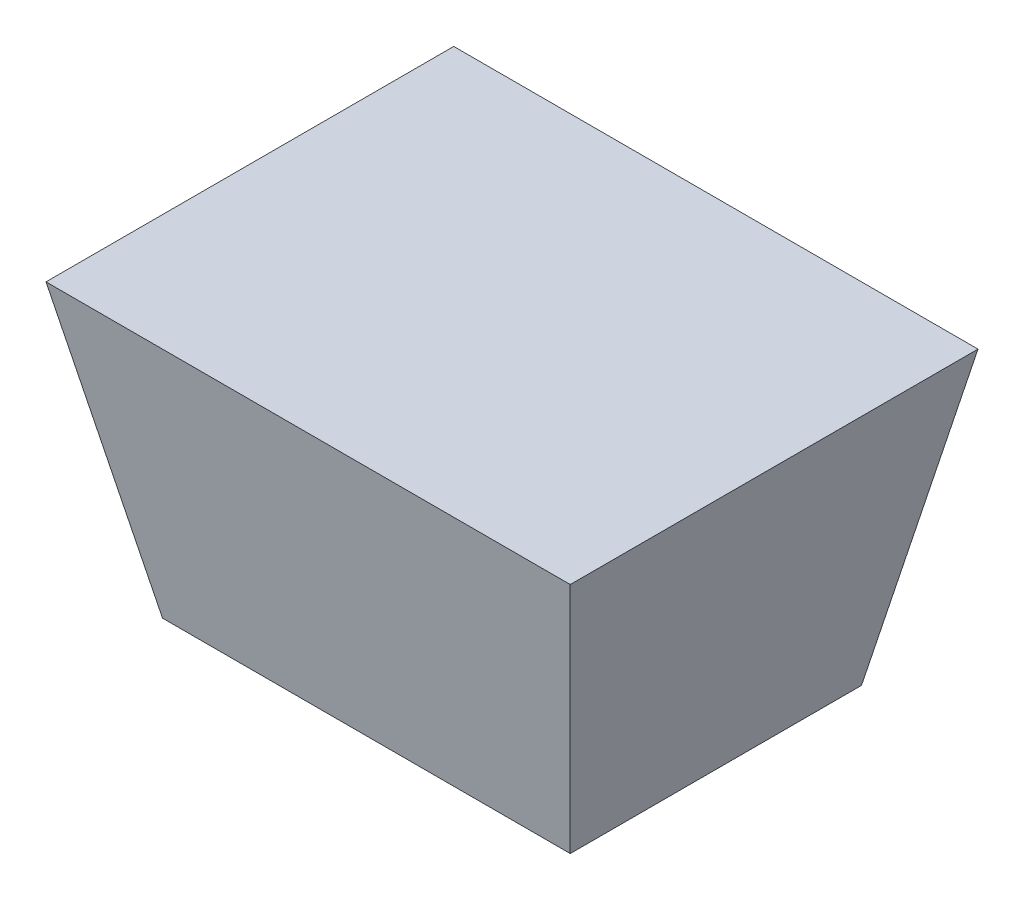
SolidWorks part; units mm, degrees
ref_plane "Front Plane" through (0, 0, 0) normal (0, 0, 1) x (1, 0, 0)
ref_plane "Top Plane" through (0, 0, 0) normal (0, 1, 0) x (1, 0, 0)
ref_plane "Right Plane" through (0, 0, 0) normal (1, 0, 0) x (0, 0, -1)
sketch "Sketch1" plane through (0, 0, 0) normal (0, 1, 0) x (1, 0, 0)
  line L1 (-35, 25) -> (35, 25)
  line L2 (-35, 25) -> (-35, -25)
  line L3 (-35, -25) -> (35, -25)
  line L4 (35, 25) -> (35, -25)
  line L5 (-35, 25) -> (35, -25) construction
  line L6 (-35, -25) -> (35, 25) construction
  point P0 (0, 0)
ref_plane "Plane1" through (0, 50, 0) normal (0, 1, 0) x (1, 0, 0)
sketch "Sketch2" plane through (0, 50, 0) normal (0, 1, 0) x (1, 0, 0)
  line L1 (-45, 35) -> (45, 35)
  line L2 (-45, 35) -> (-45, -35)
  line L3 (-45, -35) -> (45, -35)
  line L4 (45, 35) -> (45, -35)
  line L5 (-45, 35) -> (45, -35) construction
  line L6 (-45, -35) -> (45, 35) construction
  point P0 (0, 0)
loft "Loft2" add profiles "Sketch2", "Sketch1"
